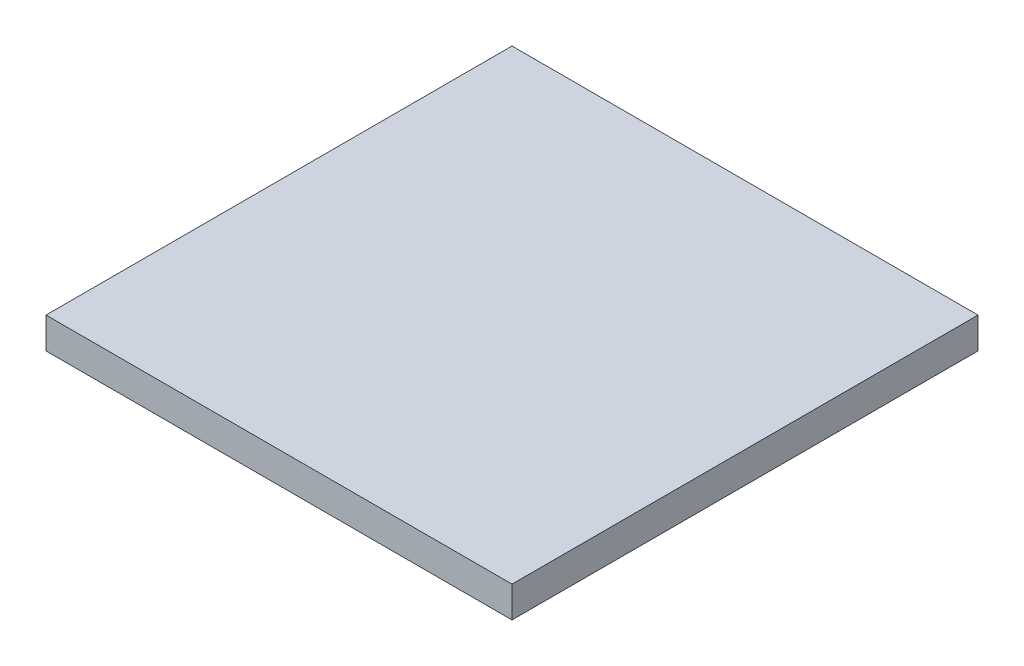
SolidWorks part; units mm, degrees
ref_plane "Front Plane" through (0, 0, 0) normal (0, 0, 1) x (1, 0, 0)
ref_plane "Top Plane" through (0, 0, 0) normal (0, 1, 0) x (1, 0, 0)
ref_plane "Right Plane" through (0, 0, 0) normal (1, 0, 0) x (0, 0, -1)
sketch "Sketch1" plane through (0, 0, 0) normal (0, 1, 0) x (1, 0, 0)
  line L1 (15, -15) -> (-15, -15)
  line L2 (15, -15) -> (15, 15)
  line L3 (15, 15) -> (-15, 15)
  line L4 (-15, -15) -> (-15, 15)
  line L5 (15, -15) -> (-15, 15) construction
  line L6 (15, 15) -> (-15, -15) construction
  point P0 (0, 0)
  dimension "D1" = 30
  dimension "D2" = 30
extrude "Boss-Extrude1" add sketch "Sketch1" along normal blind 2
